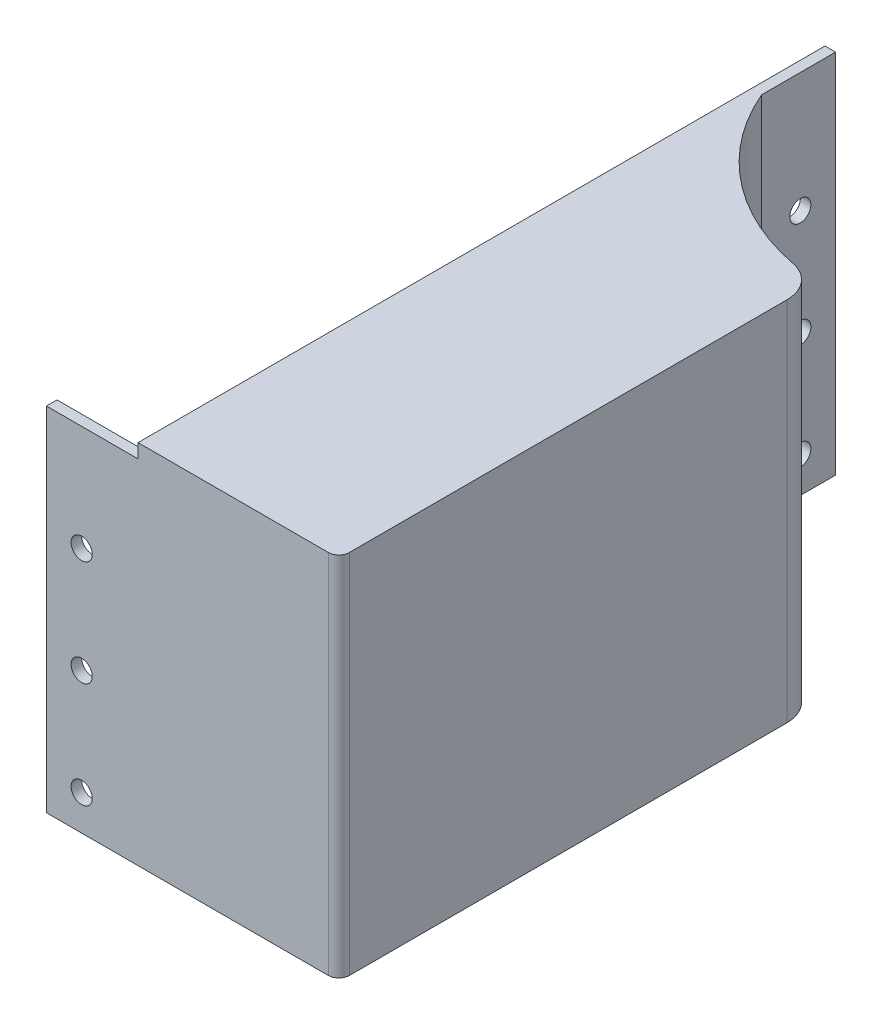
SolidWorks part; units mm, degrees
ref_plane "Спереди" through (0, 0, 0) normal (0, 0, 1) x (1, 0, 0)
ref_plane "Сверху" through (0, 0, 0) normal (0, 1, 0) x (1, 0, 0)
ref_plane "Справа" through (0, 0, 0) normal (1, 0, 0) x (0, 0, -1)
sketch "Эскиз1" plane through (0, 0, 0) normal (0, 1, 0) x (1, 0, 0)
  line L0 (0, 152.2726) -> (0, 176.2726)
  line L1 (0, 176.2726) -> (3, 176.2726)
  line L2 (3, 176.2726) -> (3, 155.2726)
  line L3 (57, 117.2726) -> (57, -18.7274)
  line L4 (57, -18.7274) -> (-26, -18.7274)
  line L5 (-26, -18.7274) -> (-26, -15.7274)
  line L6 (-26, -15.7274) -> (54, -15.7274)
  line L7 (54, -15.7274) -> (54, 112.2726)
  arc A0 (57, 117.2726) -> (3, 155.2726) centre (60.7261, 179.9361) cw
  arc A1 (54, 112.2726) -> (0, 152.2726) centre (58.5616, 174.8808) cw
  point P12 (-1.2053, 156.2726)
  point P15 (0, 0)
  dimension "D1" = 3
  dimension "D2" = 3
  dimension "D3" = 128
  dimension "D4" = 80
  dimension "D5" = 3
  dimension "D6" = 24
  dimension "D7" = 54
  dimension "D8" = 64
  dimension "D9" = 136
  dimension "D10" = 21
extrude "Бобышка-Вытянуть1" add sketch "Эскиз1" along normal blind 100
fillet "Скругление1" radius 10 1 edges at (57, 50, -117.2726)
fillet "Скругление2" radius 3 1 edges at (57, 50, 18.7274)
sketch "Эскиз2" plane through (0, 0, 18.7274) normal (0, 0, 1) x (1, 0, 0)
  line L0 (-16, 62.0104) -> (-16, -2.8896) construction
  line L1 (-26, 100) -> (-26, 0) construction
  line L2 (-26, 0) -> (54, 0) construction
  circle A0 centre (-16, 70) radius 3
  circle A1 centre (-16, 40) radius 3
  circle A2 centre (-16, 10) radius 3
  dimension "D2" = 3
  dimension "D4" = 30
  dimension "D1" = 10
  dimension "D3" = 10
extrude "Вырез-Вытянуть1" cut sketch "Эскиз2" against normal blind 60
sketch "Эскиз3" plane through (3, 0, 0) normal (1, 0, 0) x (0, 0, -1)
  line L0 (166.2726, 70.7958) -> (166.2726, -27.9988) construction
  line L1 (176.2726, 100) -> (176.2726, 0) construction
  line L2 (155.2726, 0) -> (176.2726, 0) construction
  circle A0 centre (166.2726, 10) radius 3
  circle A1 centre (166.2726, 40) radius 3
  circle A2 centre (166.2726, 70) radius 3
  dimension "D2" = 10
  dimension "D4" = 30
  dimension "D1" = 10
  dimension "D3" = 3
extrude "Вырез-Вытянуть2" cut sketch "Эскиз3" against normal blind 60
fillet "Скругление3" radius 5 1 edges at (54, 50, -112.2726)
sketch "Эскиз4" plane through (0, 100, 0) normal (0, 1, 0) x (1, 0, 0)
  line L0 (3, 176.2726) -> (0, 176.2726)
  line L1 (0, 176.2726) -> (0, -18.7274)
  line L2 (-26, -18.7274) -> (54, -18.7274) construction
  line L3 (0, -18.7274) -> (54, -18.7274)
  line L5 (57, -15.7274) -> (57, 108.4681)
  line L8 (3, 155.2726) -> (3, 176.2726)
  arc A1 (3, 155.2726) -> (48.8861, 118.2886) centre (60.7261, 179.9361) ccw construction
  arc A2 (3, 155.2726) -> (48.8861, 118.2886) centre (60.7261, 179.9361) ccw
  arc A3 (57, 108.4681) -> (48.8861, 118.2886) centre (47, 108.4681) ccw construction
  arc A4 (57, 108.4681) -> (48.8861, 118.2886) centre (47, 108.4681) ccw
  arc A5 (54, -18.7274) -> (57, -15.7274) centre (54, -15.7274) ccw construction
  arc A6 (54, -18.7274) -> (57, -15.7274) centre (54, -15.7274) ccw
extrude "Бобышка-Вытянуть2" add sketch "Эскиз4" along normal blind 4
